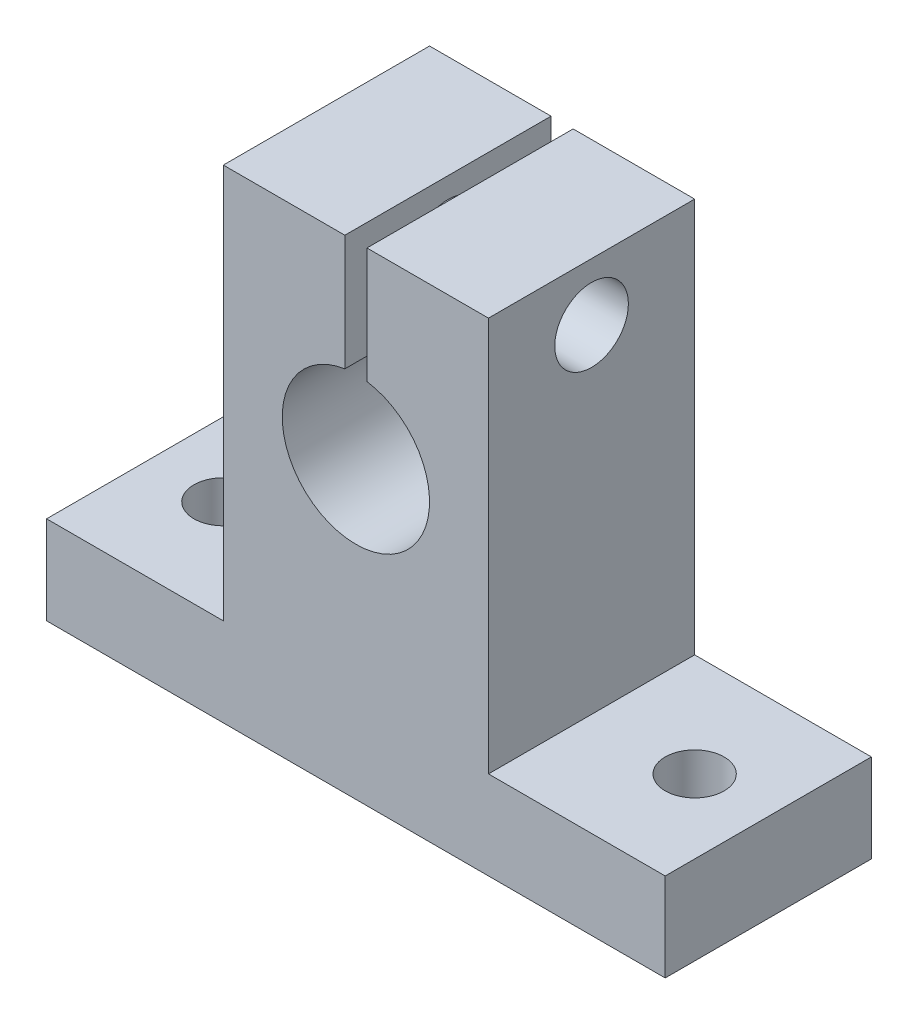
SolidWorks part; units mm, degrees
ref_plane "Front Plane" through (0, 0, 0) normal (0, 0, 1) x (1, 0, 0)
ref_plane "Top Plane" through (0, 0, 0) normal (0, 1, 0) x (1, 0, 0)
ref_plane "Right Plane" through (0, 0, 0) normal (1, 0, 0) x (0, 0, -1)
sketch "Sketch1" plane through (0, 0, 0) normal (0, 0, 1) x (1, 0, 0)
  line L0 (-21, -16.4) -> (21, -16.4)
  line L2 (-9, -10.4) -> (-9, 16.4)
  line L3 (-9, 16.4) -> (-0.75, 16.4)
  line L4 (9, -10.4) -> (9, 16.4)
  line L5 (0.75, 8.5434) -> (0.75, 16.4)
  line L6 (-0.75, 8.5434) -> (-0.75, 16.4)
  line L9 (9, -10.4) -> (21, -10.4)
  line L10 (21, -16.4) -> (21, -10.4)
  line L13 (-9, -10.4) -> (-21, -10.4)
  line L14 (-21, -16.4) -> (-21, -10.4)
  line L15 (0.75, 16.4) -> (9, 16.4)
  arc A0 (-0.75, 8.5434) -> (0.75, 8.5434) centre (0, 3.6) ccw
  point P2 (0, -16.4)
  dimension "D5" = 10
  dimension "D1" = 42
  dimension "D2" = 18
  dimension "D3" = 6
  dimension "D4" = 20
  dimension "D6" = 32.8
  dimension "D7" = 16.4
  dimension "D8" = 1.5
extrude "Boss-Extrude1" add sketch "Sketch1" along normal blind 14
sketch "Sketch2" plane through (9, 0, 0) normal (1, 0, 0) x (0, 0, -1)
  line L0 (-14, 16.4) -> (0, 16.4) construction
  circle A0 centre (-7, 12.5) radius 2.5
  dimension "D1" = 5
  dimension "D2" = 3.9
extrude "Cut-Extrude1" cut sketch "Sketch2" against normal through all
sketch "Sketch3" plane through (0, -10.4, 0) normal (0, 1, 0) x (1, 0, 0)
  line L0 (-21, -14) -> (-21, 0) construction
  line L1 (21, -14) -> (21, 0) construction
  circle A0 centre (-16, -7) radius 2
  circle A1 centre (16, -7) radius 2
  point P4 (0, 0)
  point P5 (0, 0)
  point P8 (-21, -7)
  dimension "D1" = 32
  dimension "D2" = 5
  dimension "D3" = 4
extrude "Cut-Extrude2" cut sketch "Sketch3" against normal blind 14
